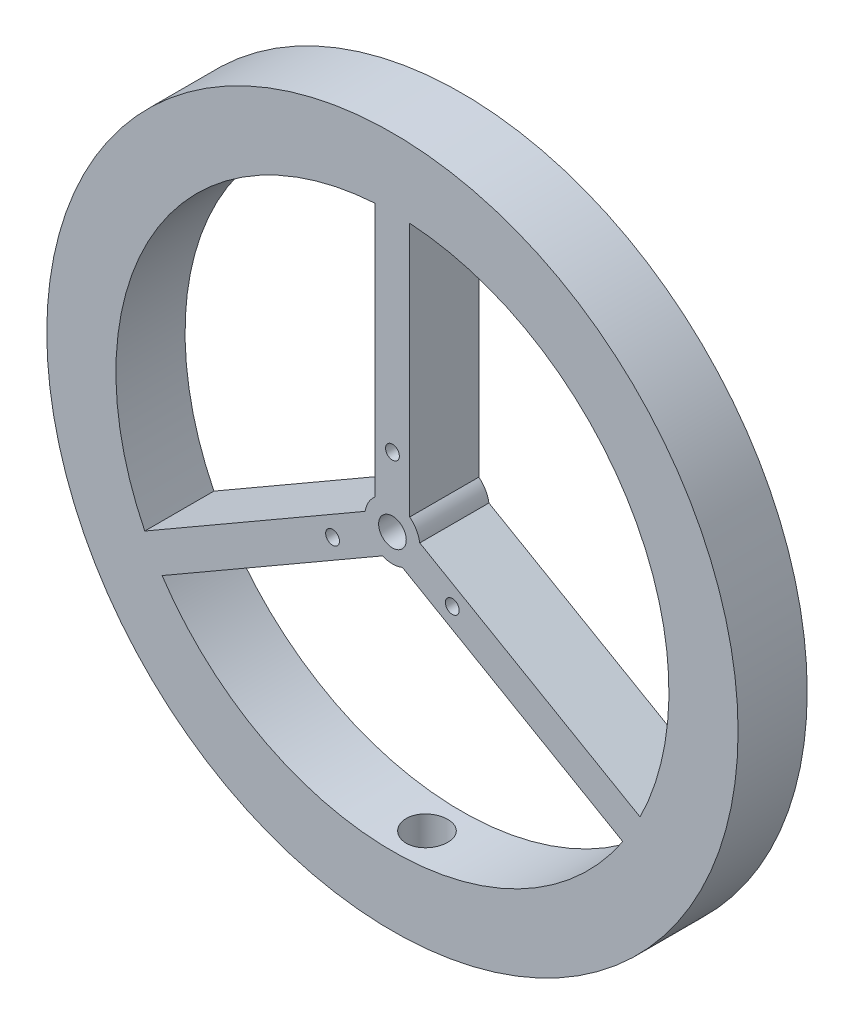
SolidWorks part; units mm, degrees
ref_plane "Front Plane" through (0, 0, 0) normal (0, 0, 1) x (1, 0, 0)
ref_plane "Top Plane" through (0, 0, 0) normal (0, 1, 0) x (1, 0, 0)
ref_plane "Right Plane" through (0, 0, 0) normal (1, 0, 0) x (0, 0, -1)
sketch "Sketch1" plane through (0, 0, 0) normal (0, 0, 1) x (1, 0, 0)
  line L1 (0, 10) -> (0, 0) construction
  line L2 (0, 0) -> (8.6603, -5) construction
  line L3 (0, 0) -> (-8.6603, -5) construction
  circle A1 centre (0, 10) radius 1
  circle A4 centre (0, 0) radius 2
  circle A5 centre (-8.6603, -5) radius 1
  circle A6 centre (8.6603, -5) radius 1
  dimension "D1" = 4
  dimension "D2" = 2
  dimension "D3" = 10
sketch "Sketch2" plane through (0, 0, 0) normal (0, 0, 1) x (1, 0, 0)
  line L2 (2.5, 39.9218) -> (2.5, 3.1225)
  line L4 (-2.5, 39.9218) -> (-2.5, 3.1225)
  line L5 (3.9542, 0.6038) -> (35.8233, -17.7958)
  line L7 (33.3233, -22.126) -> (1.4542, -3.7263)
  line L8 (0, 0) -> (0, 113.6326) construction
  line L9 (0, 0) -> (59.8703, -34.5661) construction
  line L10 (0, 0) -> (-67.4581, -38.947) construction
  line L12 (-1.4542, -3.7263) -> (-33.3233, -22.126)
  line L14 (-35.8233, -17.7958) -> (-3.9542, 0.6038)
  arc A0 (-2.5, 39.9218) -> (-35.8233, -17.7958) centre (0, 0) ccw
  circle A1 centre (0, 0) radius 50
  arc A2 (-1.4542, -3.7263) -> (1.4542, -3.7263) centre (0, 0) ccw
  arc A3 (-33.3233, -22.126) -> (33.3233, -22.126) centre (0, 0) ccw
  arc A4 (35.8233, -17.7958) -> (2.5, 39.9218) centre (0, 0) ccw
  arc A5 (-2.5, 3.1225) -> (-3.9542, 0.6038) centre (0, 0) ccw
  arc A6 (3.9542, 0.6038) -> (2.5, 3.1225) centre (0, 0) ccw
  dimension "D1" = 100
  dimension "D2" = 80
  dimension "D3" = 8
extrude "Boss-Extrude1" add sketch "Sketch2" along normal blind 10
extrude "Cut-Extrude2" cut sketch "Sketch1" along normal through all
sketch "Sketch3" plane through (0, 0, 0) normal (0, 1, 0) x (1, 0, 0)
  circle A0 centre (0, -5) radius 3
  dimension "D1" = 6
  dimension "D2" = 5
extrude "Cut-Extrude3" cut sketch "Sketch3" against normal through all from offset 10
